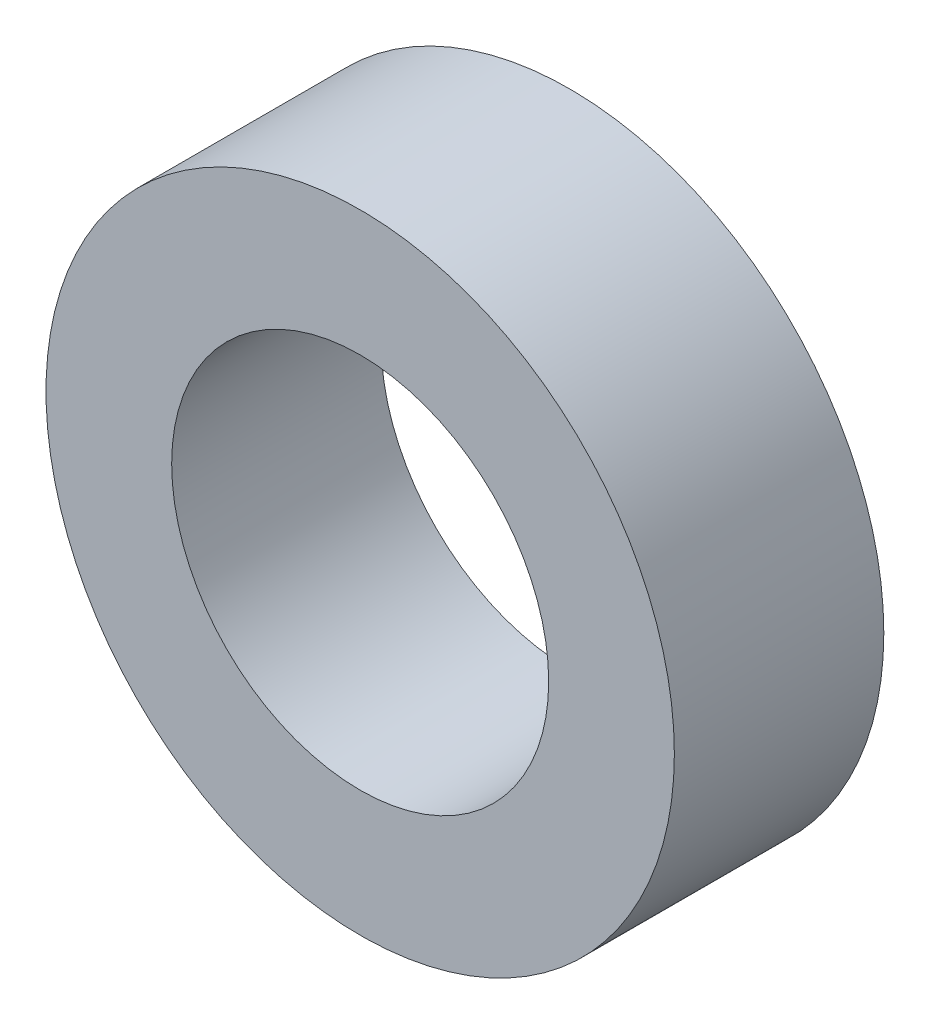
SolidWorks part; units mm, degrees
ref_plane "Front Plane" through (0, 0, 0) normal (0, 0, 1) x (1, 0, 0)
ref_plane "Top Plane" through (0, 0, 0) normal (0, 1, 0) x (1, 0, 0)
ref_plane "Right Plane" through (0, 0, 0) normal (1, 0, 0) x (0, 0, -1)
sketch "Sketch1" plane through (0, 0, 0) normal (0, 0, 1) x (1, 0, 0)
  circle A0 centre (0, 0) radius 4.5
  circle A1 centre (0, 0) radius 7.5
  dimension "D1" = 9
  dimension "D2" = 3
extrude "Boss-Extrude1" add sketch "Sketch1" along normal blind 5
